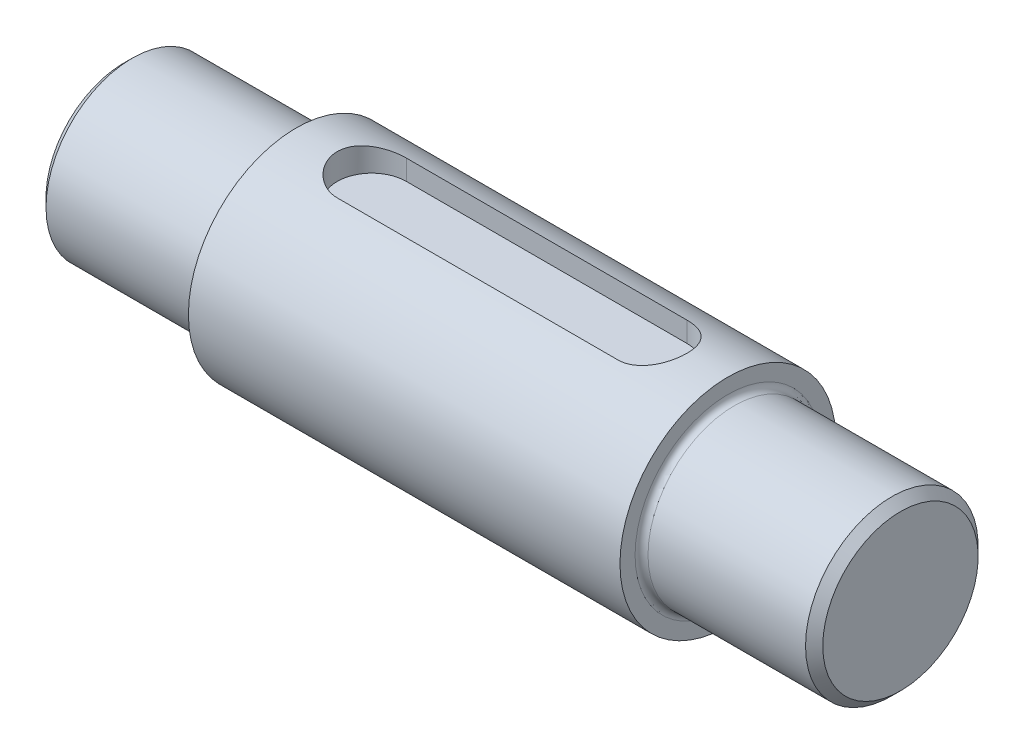
SolidWorks part; units mm, degrees
ref_plane "Front" through (0, 0, 0) normal (0, 0, 1) x (1, 0, 0)
ref_plane "Top" through (0, 0, 0) normal (0, 1, 0) x (1, 0, 0)
ref_plane "Right" through (0, 0, 0) normal (1, 0, 0) x (0, 0, -1)
sketch "Esquisse1" plane through (0, 0, 0) normal (0, 1, 0) x (1, 0, 0)
  line L0 (90, 0) -> (-90, 0) construction
  line L1 (-90, 0) -> (-90, 20)
  line L2 (-90, 20) -> (-51.5, 20)
  line L3 (-50, 21.5) -> (-50, 25)
  line L4 (-50, 25) -> (50, 25)
  line L5 (0, 25) -> (0, 0) construction
  line L6 (50, 21.5) -> (50, 25)
  line L7 (90, 20) -> (51.5, 20)
  line L8 (90, 0) -> (90, 20)
  line L9 (-90, 0) -> (90, 0)
  arc A0 (-51.5, 20) -> (-50, 21.5) centre (-51.5, 21.5) ccw
  arc A1 (51.5, 20) -> (50, 21.5) centre (51.5, 21.5) cw
  point P4 (0, 0)
  dimension "D3" = 1.5
  dimension "D1" = 90
  dimension "D2" = 50
  dimension "D4" = 20
  dimension "D5" = 25
revolve "Révolution1" add sketch "Esquisse1" angle 360 about L9
chamfer "Chanfrein1" distance 2 angle 45 2 edges at (-90, 0, 20) (90, 0, 20)
ref_plane "Plan1" through (0, 25, 0) normal (0, 1, 0) x (1, 0, 0)
sketch "Esquisse2" plane through (0, 25, 0) normal (0, 1, 0) x (1, 0, 0)
  line L0 (-32.5, 0) -> (32.5, 0) construction
  line L1 (-32.5, 8) -> (32.5, 8)
  line L2 (-32.5, -8) -> (32.5, -8)
  arc A0 (-32.5, 8) -> (-32.5, -8) centre (-32.5, 0) ccw
  arc A1 (32.5, -8) -> (32.5, 8) centre (32.5, 0) ccw
  point P2 (0, 0)
  dimension "D2" = 8
  dimension "D1" = 65
extrude "Enlèv. mat.-Extru.1" cut sketch "Esquisse2" against normal blind 6
